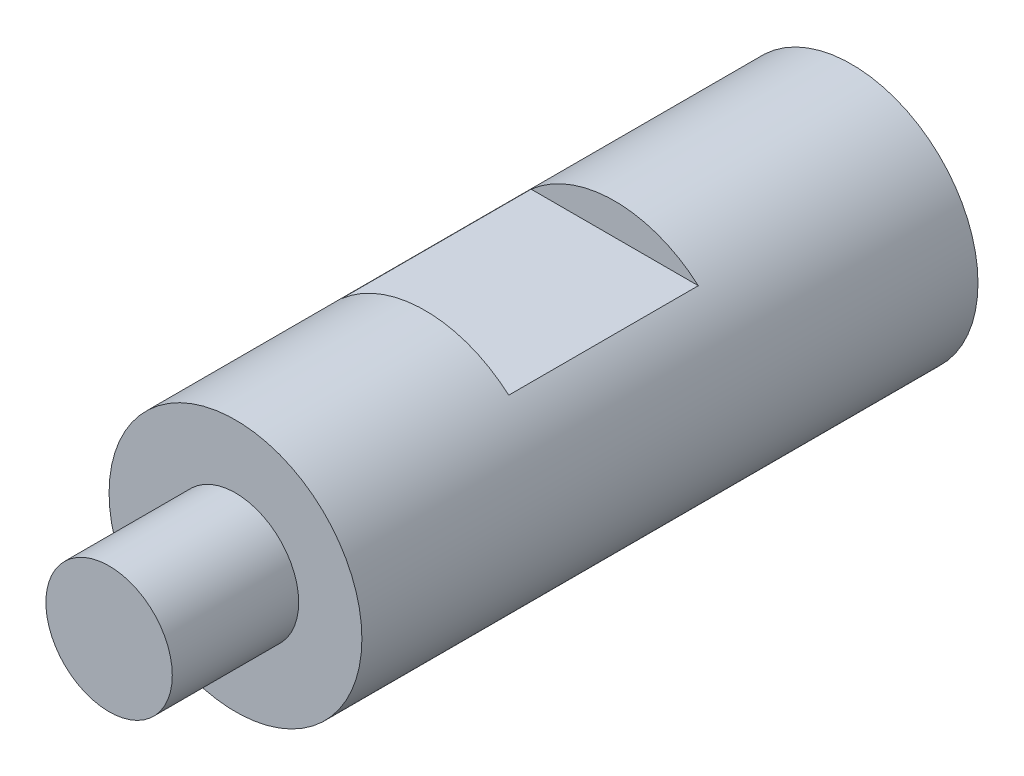
SolidWorks part; units mm, degrees
ref_plane "Front Plane" through (0, 0, 0) normal (1, 0, 0) x (0, 1, 0)
ref_plane "Top Plane" through (0, 0, 0) normal (0, 0, 1) x (0, 1, 0)
ref_plane "Right Plane" through (0, 0, 0) normal (0, 1, 0) x (-1, 0, 0)
sketch "Sketch2" plane through (0, 0, 0) normal (0, 0, 1) x (0, 1, 0)
  circle A0 centre (0, 0) radius 6.35
  dimension "D2" = 12.7
extrude "Boss-Extrude1" add sketch "Sketch2" along normal blind 30.9499
hole_wizard "Tap Drill for 1/4-20 Tap1" positions "Sketch3" profile "Sketch5" hole size "1/4-20" standard "ANSI Inch"
sketch "Sketch3" plane through (0, 0, 0) normal (0, 0, -1) x (-1, 0, 0)
  point P0 (0, 0)
sketch "Sketch5" plane through (0, 0, 0) normal (1, 0, 0) x (0, 1, 0)
  line L0 (0, 0) -> (0, 14.2338)
  line L1 (0, 14.2338) -> (2.5527, 12.7)
  line L2 (2.5527, 12.7) -> (2.5527, 0)
  line L5 (2.5527, 0) -> (0, 0)
  line L10 (0, 14.2338) -> (-2.5527, 12.7) construction
  line L11 (0, -6.35) -> (0, 107.95) construction
  dimension "Hole Dia." = 5.1054
  dimension "Hole Depth" = 12.7
  dimension "Drill Angle" = 118
sketch "Sketch6" plane through (0, 0, 30.9499) normal (0, 0, 1) x (1, 0, 0)
  circle A0 centre (0, 0) radius 3.175
  dimension "D1" = 6.35
extrude "Boss-Extrude2" add sketch "Sketch6" along normal blind 6.35
sketch "Sketch7" plane through (0, 0, 0) normal (1, 0, 0) x (0, 1, 0)
  line L0 (-6.35, 30.9499) -> (-6.35, 0) construction
  line L1 (-6.35, 21.4249) -> (6.35, 21.4249)
  line L2 (-6.35, 21.4249) -> (-6.35, 11.8999)
  line L3 (-6.35, 11.8999) -> (6.35, 11.8999)
  line L4 (6.35, 21.4249) -> (6.35, 11.8999)
  line L5 (6.35, 0) -> (6.35, 30.9499) construction
  line L6 (6.35, 30.9499) -> (-6.35, 30.9499) construction
  line L7 (0, 21.4249) -> (0, 11.8999) construction
  line L8 (-4.7625, 21.4249) -> (4.7625, 21.4249)
  line L9 (-4.7625, 21.4249) -> (-4.7625, 11.8999)
  line L10 (-4.7625, 11.8999) -> (4.7625, 11.8999)
  line L11 (4.7625, 21.4249) -> (4.7625, 11.8999)
  line L12 (-4.7625, 21.4249) -> (4.7625, 11.8999) construction
  point P16 (0, 16.6624)
  point P17 (0, 16.6624)
  dimension "D1" = 9.525
  dimension "D2" = 9.525
  dimension "D3" = 9.525
extrude "Cut-Extrude1" cut sketch "Sketch7" against normal through all and the other way through all contours L9 L1 L2 L3 | L1 L11 L3 L4
ref_plane "Plane2" through (0, 0, 30.9499) normal (0, 0, 1) x (1, 0, 0)
ref_plane "Plane3" through (4.2001, 0, 0) normal (-1, 0, 0) x (0, 0, 1)
